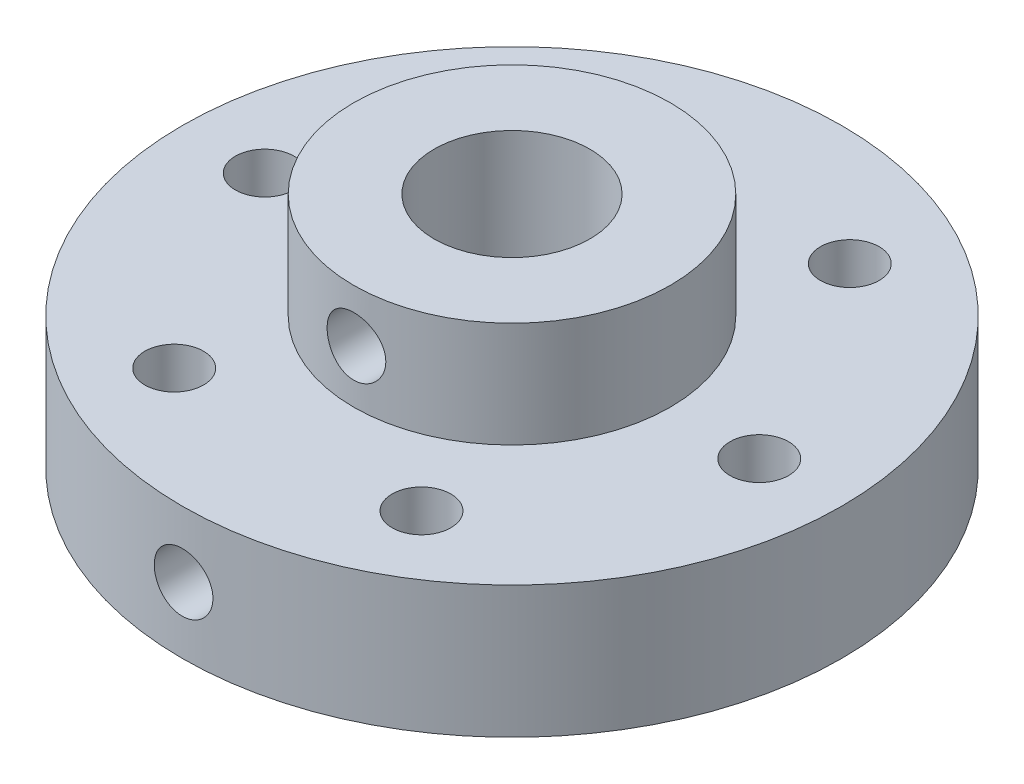
SolidWorks part; units mm, degrees
material "6063-O"
ref_plane "Front Plane" through (0, 0, 0) normal (0, 0, 1) x (1, 0, 0)
ref_plane "Top Plane" through (0, 0, 0) normal (0, 1, 0) x (1, 0, 0)
ref_plane "Right Plane" through (0, 0, 0) normal (1, 0, 0) x (0, 0, -1)
sketch "Sketch1" plane through (0, 0, 0) normal (0, 1, 0) x (1, 0, 0)
  circle A0 centre (0, 0) radius 12.7
  dimension "D1" = 25.4
extrude "Boss-Extrude1" add sketch "Sketch1" along normal blind 5.08
sketch "Sketch2" plane through (0, 5.08, 0) normal (0, 1, 0) x (1, 0, 0)
  circle A0 centre (0, 0) radius 6.096
  dimension "D1" = 12.192
extrude "Boss-Extrude2" add sketch "Sketch2" along normal blind 4.064
sketch "Sketch3" plane through (0, 9.144, 0) normal (0, 1, 0) x (1, 0, 0)
  circle A0 centre (0, 0) radius 3
  dimension "D1" = 6
extrude "Cut-Extrude1" cut sketch "Sketch3" against normal through all
sketch "Sketch4" plane through (0, 0, 0) normal (0, 0, 1) x (1, 0, 0)
  line L0 (0, 0) -> (0, 9.144) construction
  line L1 (3, 9.144) -> (-3, 9.144) construction
  line L2 (6.096, 9.144) -> (-6.096, 9.144) construction
  circle A0 centre (0, 7.112) radius 1.5875
  circle A1 centre (0, 2.54) radius 1.5875
  dimension "D1" = 3.175
  dimension "D2" = 2.032
  dimension "D3" = 2.54
hole_wizard "#4-40 Tapped Hole1" positions "Sketch5" profile "Sketch7" tap size "#4-40" standard "ANSI Inch"
sketch "Sketch5" plane through (0, 0, 0) normal (0, 0, 1) x (1, 0, 0)
  point P0 (0, 7.112)
  point P3 (0, 2.54)
sketch "Sketch7" plane through (0, 7.112, 0) normal (1, 0, 0) x (0, 1, 0)
  line L0 (0, 0) -> (0, 12.7)
  line L1 (0, 12.7) -> (1.1303, 12.7)
  line L2 (1.1303, 12.7) -> (1.1303, 0)
  line L5 (1.1303, 0) -> (0, 0)
  line L11 (0, -6.35) -> (0, 107.95) construction
  dimension "Thru Tap Drill Dia." = 2.2606
  dimension "Thru Tap Drill Depth" = 12.7
cosmetic thread "Hole Thread1" parameters "D2"=2.8448
cosmetic thread "Hole Thread2" parameters "D2"=2.8448
sketch "Sketch8" plane through (0, 0, 0) normal (0, -1, 0) x (1, 0, 0)
  circle A0 centre (0, 0) radius 9.525 construction
  circle A1 centre (-9.525, 0) radius 1.5875
  circle A2 centre (-4.7625, 8.2489) radius 1.5875
  circle A3 centre (4.7625, 8.2489) radius 1.5875
  circle A4 centre (9.525, 0) radius 1.5875
  circle A5 centre (4.7625, -8.2489) radius 1.5875
  circle A6 centre (-4.7625, -8.2489) radius 1.5875
  point P17 (0, 0)
  dimension "D1" = 19.05
  dimension "D2" = 3.175
  dimension "D3" = 6
hole_wizard "#4-40 Tapped Hole2" positions "Sketch9" profile "Sketch10" tap size "#4-40" standard "ANSI Inch" end condition through all
sketch "Sketch9" plane through (0, 0, 0) normal (0, -1, 0) x (-1, 0, 0)
  point P0 (9.525, 0)
  point P3 (4.7625, -8.2489)
  point P6 (-4.7625, -8.2489)
  point P9 (-9.525, 0)
  point P12 (-4.7625, 8.2489)
  point P15 (4.7625, 8.2489)
sketch "Sketch10" plane through (-9.525, 0, 0) normal (1, 0, 0) x (0, 0, -1)
  line L0 (0, 0) -> (0, 9.144)
  line L1 (0, 9.144) -> (1.1303, 9.144)
  line L2 (1.1303, 9.144) -> (1.1303, 0)
  line L5 (1.1303, 0) -> (0, 0)
  line L11 (0, -6.35) -> (0, 107.95) construction
  dimension "Thru Tap Drill Dia." = 2.2606
  dimension "Thru Tap Drill Depth" = 9.144
cosmetic thread "Hole Thread3" parameters "D2"=2.8448
cosmetic thread "Hole Thread4" parameters "D2"=2.8448
cosmetic thread "Hole Thread5" parameters "D2"=2.8448
cosmetic thread "Hole Thread6" parameters "D2"=2.8448
cosmetic thread "Hole Thread7" parameters "D2"=2.8448
cosmetic thread "Hole Thread8" parameters "D2"=2.8448
